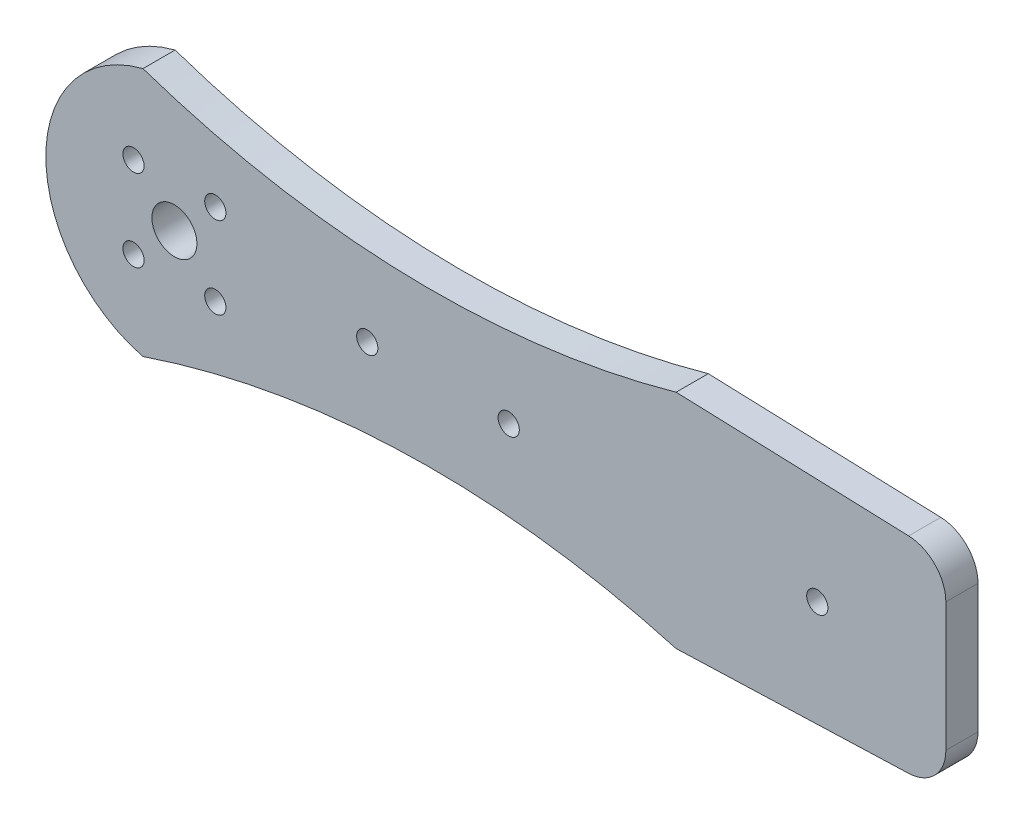
SolidWorks part; units mm, degrees
ref_plane "Спереди" through (0, 0, 0) normal (0, 0, 1) x (1, 0, 0)
ref_plane "Сверху" through (0, 0, 0) normal (0, 1, 0) x (1, 0, 0)
ref_plane "Справа" through (0, 0, 0) normal (1, 0, 0) x (0, 0, -1)
other "Configuration Table"
sketch "Eskiz_kontur" plane through (0, 0, 0) normal (0, 0, 1) x (1, 0, 0)
  line L0 (78.0435, 17.2681) -> (114.2094, 15.9963)
  line L1 (120, 10) -> (120, -10)
  line L2 (114.2094, -15.9963) -> (78.0435, -17.2681)
  arc A0 (78.0435, -17.2681) -> (-4.8917, -19.3926) centre (40, -152) ccw
  arc A1 (-4.8917, -19.3926) -> (-4.8917, 19.3926) centre (0, 0) cw
  arc A2 (-4.8917, 19.3926) -> (78.0435, 17.2681) centre (40, 152) ccw
  arc A3 (114.2094, 15.9963) -> (120, 10) centre (114, 10) cw
  arc A4 (120, -10) -> (114.2094, -15.9963) centre (114, -10) cw
extrude "Plastina" add sketch "Eskiz_kontur" along normal blind 5
sketch "Eskiz_otverstiya" plane through (0, 0, 0) normal (0, 0, 1) x (1, 0, 0)
  circle A0 centre (-6.364, -6.364) radius 1.65
  circle A1 centre (6.364, -6.364) radius 1.65
  circle A2 centre (0, 0) radius 3.5
  circle A3 centre (30, 0) radius 1.65
  circle A4 centre (-6.364, 6.364) radius 1.65
  circle A5 centre (6.364, 6.364) radius 1.65
  circle A6 centre (52, 0) radius 1.65
  circle A7 centre (100, 0) radius 1.65
  dimension "d1" = 3.3
  dimension "d2" = 3.3
  dimension "d3" = 7
  dimension "d4" = 3.3
  dimension "d5" = 3.3
  dimension "d6" = 3.3
  dimension "d7" = 3.3
  dimension "d8" = 3.3
extrude "Otverstiya" cut sketch "Eskiz_otverstiya" against normal through all and the other way through all
equation "\"T3\" = 3"
equation "\"T5\" = 5"
equation "\"D_M3\" = 3.3"
equation "\"D_M2\" = 2.2"
equation "\"D_M3_TAP\" = 2.5"
equation "\"D_M4\" = 4.5"
equation "\"L1\" = 100"
equation "\"L2\" = 100"
equation "\"D1@Plastina\" = \"T5\""
equation "\"d1@Eskiz_otverstiya\" = \"D_M3\""
equation "\"d2@Eskiz_otverstiya\" = \"D_M3\""
equation "\"d4@Eskiz_otverstiya\" = \"D_M3\""
equation "\"d5@Eskiz_otverstiya\" = \"D_M3\""
equation "\"d6@Eskiz_otverstiya\" = \"D_M3\""
equation "\"d7@Eskiz_otverstiya\" = \"D_M3\""
equation "\"d8@Eskiz_otverstiya\" = \"D_M3\""
